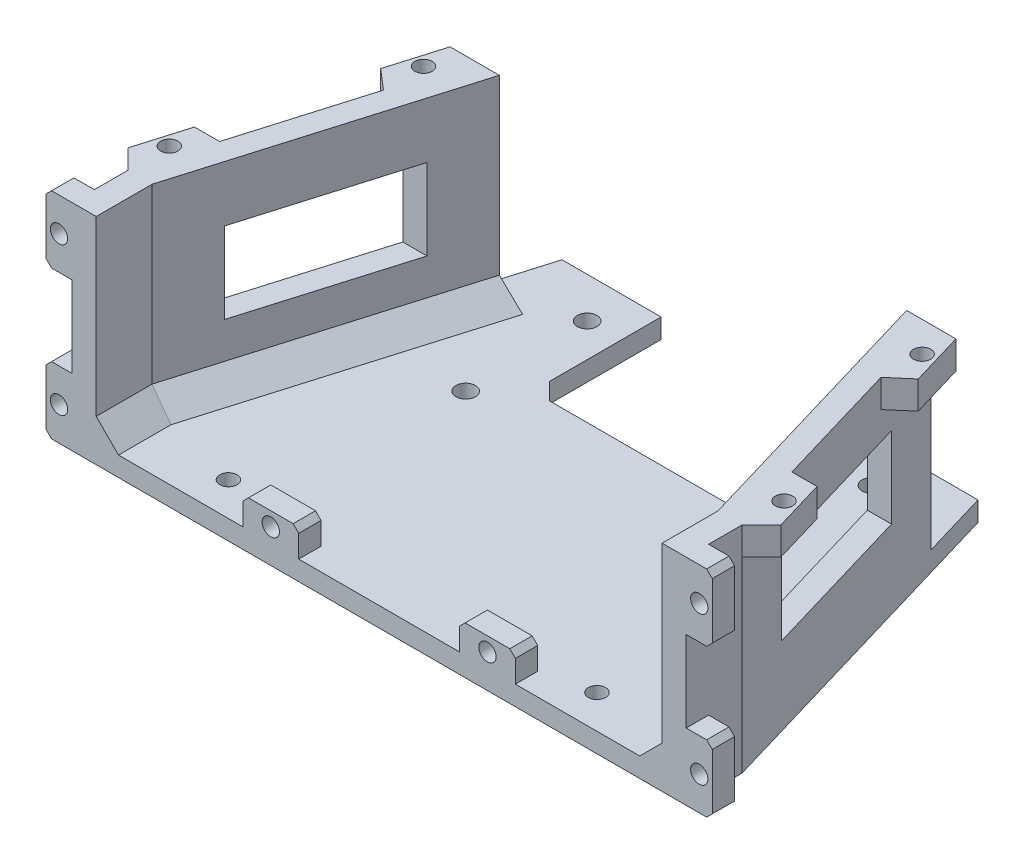
SolidWorks part; units mm, degrees
ref_plane "Front Plane" through (0, 0, 0) normal (0, 0, 1) x (1, 0, 0)
ref_plane "Top Plane" through (0, 0, 0) normal (0, 1, 0) x (1, 0, 0)
ref_plane "Right Plane" through (0, 0, 0) normal (1, 0, 0) x (0, 0, -1)
sketch "Sketch1" plane through (0, 0, 0) normal (0, 1, 0) x (1, 0, 0)
  line L0 (35.5, 70) -> (35.5, 46.9995)
  line L1 (0, 0) -> (110, 0)
  line L2 (0, 0) -> (0, 70)
  line L3 (0, 70) -> (35.5, 70)
  line L4 (110, 0) -> (110, 70)
  line L5 (35.5, 46.9995) -> (74.5, 46.9995)
  line L6 (74.5, 46.9995) -> (74.5, 70)
  line L7 (74.5, 70) -> (110, 70)
  dimension "D1" = 110
  dimension "D2" = 23.0005
  dimension "30" = 35.5
  dimension "D3" = 35.5
  dimension "D4" = 39
  dimension "60" = 70
extrude "Boss-Extrude1" add sketch "Sketch1" along normal blind 3.5
fillet "Fillet1" radius 3 2 edges at (35.5, 1.75, -46.9995) (74.5, 1.75, -46.9995) profile chamfer
sketch "Sketch3" plane through (0, 0, 0) normal (0, 0, 1) x (1, 0, 0)
  line L0 (55, 0) -> (55, 31.9215) construction
  line L1 (0, 0) -> (110, 0) construction
sketch "Sketch4" plane through (0, 3.5, 0) normal (0, 1, 0) x (1, 0, 0)
  line L0 (55, 46.9995) -> (55, 0) construction
  line L1 (71.5, 46.9995) -> (38.5, 46.9995) construction
  line L2 (0, 0) -> (110, 0) construction
  line L3 (110, 10) -> (105.67, 10)
  line L4 (0, 0) -> (4.33, 0)
  line L5 (0, 0) -> (0, 10)
  line L6 (0, 10) -> (4.33, 10)
  line L7 (4.33, 0) -> (4.33, 10)
  line L8 (105.67, 0) -> (105.67, 10)
  line L9 (110, 0) -> (105.67, 0)
  line L10 (110, 0) -> (110, 10)
  dimension "D1" = 4.33
  dimension "10" = 10
extrude "Boss-Extrude2" add sketch "Sketch4" along normal blind 35
sketch "Sketch5" plane through (0, 0, 0) normal (0, 0, 1) x (1, 0, 0)
  line L0 (4.33, 3.5) -> (105.67, 3.5) construction
  line L1 (40.6, 3.5) -> (30.6, 3.5)
  line L2 (40.6, 3.5) -> (40.6, 8.5)
  line L3 (40.6, 8.5) -> (30.6, 8.5)
  line L4 (30.6, 3.5) -> (30.6, 8.5)
  line L5 (55, 0) -> (55, 31.9215) construction
  line L6 (-2.3294, 38.5) -> (-2.3294, 26.5) construction
  line L7 (0, 38.5) -> (-4.6587, 38.5)
  line L8 (0, 38.5) -> (0, 26.5)
  line L9 (0, 26.5) -> (-4.6587, 26.5)
  line L10 (-4.6587, 38.5) -> (-4.6587, 26.5)
  line L11 (0, 0) -> (-4.6587, 0)
  line L12 (0, 0) -> (0, 12)
  line L13 (0, 12) -> (-4.6587, 12)
  line L14 (-4.6587, 0) -> (-4.6587, 12)
  line L15 (-2.3294, 26.5) -> (-2.3294, 12) construction
  line L16 (-2.3294, 12) -> (-2.3294, 0) construction
  line L17 (-2.3294, 0) -> (30.6, 6) construction
  line L18 (30.6, 6) -> (40.6, 6) construction
  line L19 (55, 0) -> (55, 31.9215) construction
  line L20 (69.4, 8.5) -> (79.4, 8.5)
  line L21 (79.4, 3.5) -> (79.4, 8.5)
  line L22 (69.4, 3.5) -> (79.4, 3.5)
  line L23 (69.4, 3.5) -> (69.4, 8.5)
  line L24 (110, 12) -> (114.6587, 12)
  line L25 (114.6587, 0) -> (114.6587, 12)
  line L26 (110, 0) -> (114.6587, 0)
  line L27 (110, 0) -> (110, 12)
  line L28 (110, 26.5) -> (114.6587, 26.5)
  line L29 (114.6587, 38.5) -> (114.6587, 26.5)
  line L30 (110, 38.5) -> (114.6587, 38.5)
  line L31 (110, 38.5) -> (110, 26.5)
  circle A0 centre (-2.3294, 32.5) radius 1.55
  circle A1 centre (-2.3294, 6) radius 1.55
  circle A2 centre (35.6, 6) radius 1.55
  circle A3 centre (74.4, 6) radius 1.55
  circle A4 centre (112.3294, 6) radius 1.55
  circle A5 centre (112.3294, 32.5) radius 1.55
  dimension "D5" = 3.1
  dimension "D6" = 3.1
  dimension "D7" = 3.1
  dimension "D1" = 14.4
  dimension "D2" = 10
  dimension "D3" = 12
  dimension "3.5" = 5
  dimension "D4" = 12
extrude "Boss-Extrude3" add sketch "Sketch5" against normal blind 4
fillet "Fillet2" radius 1 12 edges at (114.6587, 0, -2) (114.6587, 26.5, -2) (114.6587, 38.5, -2) (114.6587, 12, -2) (79.4, 8.5, -2) (69.4, 8.5, -2) (40.6, 8.5, -2) (30.6, 8.5, -2) (-4.6587, 0, -2) (-4.6587, 12, -2) (-4.6587, 26.5, -2) (-4.6587, 38.5, -2) profile chamfer
sketch "Sketch6" plane through (0, 3.5, 0) normal (0, 1, 0) x (1, 0, 0)
  line L0 (55, 46.9995) -> (55, 73.7007) construction
  line L1 (71.5, 46.9995) -> (38.5, 46.9995) construction
  line L2 (17.75, 70) -> (92.25, 70)
  line L3 (35.5, 70) -> (74.5, 70) construction
  line L4 (110, 70) -> (74.5, 70) construction
  line L5 (92.25, 70) -> (110, 10)
  line L6 (110, 10) -> (110, 70)
  line L7 (110, 70) -> (92.25, 70)
  line L8 (17.75, 70) -> (0, 10)
  line L9 (0, 10) -> (0, 70)
  line L10 (0, 70) -> (17.75, 70)
  point P4 (55, 70)
  point P14 (55, 70)
  line M8 (110, 10) -> (110, 70)
  line M9 (110, 70) -> (74.5, 70)
  line M15 (35.5, 70) -> (0, 70)
  line M16 (0, 70) -> (0, 10)
extrude "Cut-Extrude1" cut sketch "Sketch6" against normal blind 14 contours L8 M15 M16 | L5 M9 M8
sketch "Sketch8" plane through (0, 3.5, 0) normal (0, 1, 0) x (1, 0, 0)
  line L0 (14.2, 58) -> (95.8, 58) construction
  line L1 (17.75, 70) -> (0, 10) construction
  line L2 (92.25, 70) -> (110, 10) construction
  line L3 (35.5, 70) -> (17.75, 70) construction
  line L4 (0, 10) -> (14.2, 58)
  line L5 (14.2, 58) -> (18.53, 58)
  line L6 (18.53, 58) -> (4.33, 10)
  line L7 (4.33, 10) -> (0, 10)
  line L8 (55, 58) -> (55, 0) construction
  line L9 (40.6, 0) -> (69.4, 0) construction
  line L10 (91.47, 58) -> (105.67, 10)
  line L11 (95.8, 58) -> (91.47, 58)
  line L12 (110, 10) -> (95.8, 58)
  line L13 (105.67, 10) -> (110, 10)
  dimension "D1" = 12
  dimension "D2" = 4.33
extrude "Boss-Extrude4" add sketch "Sketch8" along normal blind 35
sketch "Sketch9" plane through (0, 0, 0) normal (-1, 0, 0) x (0, 0, 1)
  line L0 (-58, 38.5) -> (-10, 38.5) construction
  line L1 (-20, 28.5) -> (-48, 28.5)
  line L2 (-20, 28.5) -> (-20, 14)
  line L3 (-20, 14) -> (-48, 14)
  line L4 (-48, 28.5) -> (-48, 14)
  line L5 (-58, 38.5) -> (-58, 3.5) construction
  line L6 (-10, 0) -> (-70, 0) construction
  line L7 (-10, 38.5) -> (-10, 0) construction
  dimension "D1" = 10
  dimension "D2" = 14
  dimension "10" = 10
  dimension "D3" = 10
extrude "Cut-Extrude2" cut sketch "Sketch9" against normal blind 117
sketch "Sketch10" plane through (0, 3.5, 0) normal (0, 1, 0) x (1, 0, 0)
  line L0 (55, 46.9995) -> (55, 72.6447) construction
  line L1 (71.5, 46.9995) -> (38.5, 46.9995) construction
  line L2 (74.5, 70) -> (74.5, 49.9995) construction
  line L3 (92.25, 70) -> (74.5, 70) construction
  circle A0 centre (80.5, 62.75) radius 1.75
  circle A1 centre (80.5, 41) radius 1.75
  circle A2 centre (29.5, 41) radius 1.75
  circle A3 centre (29.5, 62.75) radius 1.75
  dimension "D1" = 6
  dimension "D2" = 6
  dimension "D3" = 21.75
  dimension "D4" = 7.25
  dimension "D5" = 3.5
  dimension "D6" = 3.5
extrude "Cut-Extrude3" cut sketch "Sketch10" against normal blind 117
fillet "Fillet3" radius 4 4 edges at (98.57, 3.5, -34) (11.43, 3.5, -34) (4.33, 3.5, -5) (105.67, 3.5, -5) profile chamfer
sketch "Sketch11" plane through (0, 38.5, 0) normal (0, 1, 0) x (1, 0, 0)
  line L0 (55, 46.9995) -> (55, 0) construction
  line L1 (71.5, 46.9995) -> (38.5, 46.9995) construction
  line L2 (40.6, 0) -> (69.4, 0) construction
  line L3 (110, 6.01) -> (55, 6.01) construction
  line L4 (110, 4) -> (110, 10) construction
  line L5 (79.4, 0) -> (101.67, 0) construction
  circle A0 centre (88, 6.01) radius 1.55
  circle A1 centre (22, 6.01) radius 1.55
  dimension "D1" = 22
  dimension "D3" = 3.1
  dimension "D2" = 6.01
extrude "Cut-Extrude4" cut sketch "Sketch11" against normal blind 95
sketch "Sketch12" plane through (0, 38.5, 0) normal (0, 1, 0) x (1, 0, 0)
  line L0 (14.2, 58) -> (9.7, 58)
  line L1 (14.2, 58) -> (11.3632, 48.4108)
  line L4 (6.8632, 48.4108) -> (9.7, 58)
  line L5 (55, 0) -> (55, 70.416) construction
  line L7 (14.2, 58) -> (0, 10) construction
  line L8 (40.6, 0) -> (69.4, 0) construction
  line L9 (3.7502, 22.6767) -> (0.9134, 13.0875)
  line L11 (-3.4724, 13.4734) -> (-0.7498, 22.6767)
  line L12 (-0.7498, 22.6767) -> (3.7502, 22.6767)
  line L13 (6.8632, 48.4108) -> (10.45, 45.324)
  line L14 (10.45, 45.324) -> (11.3632, 48.4108)
  line L15 (-3.4724, 13.4734) -> (0, 10)
  line L16 (0, 10) -> (0.9134, 13.0875)
  line L17 (110.7498, 22.6767) -> (106.2498, 22.6767)
  line L18 (113.4724, 13.4734) -> (110.7498, 22.6767)
  line L19 (113.4724, 13.4734) -> (110, 10)
  line L20 (110, 10) -> (109.0866, 13.0875)
  line L21 (106.2498, 22.6767) -> (109.0866, 13.0875)
  line L22 (103.1368, 48.4108) -> (99.55, 45.324)
  line L23 (99.55, 45.324) -> (98.6368, 48.4108)
  line L24 (95.8, 58) -> (98.6368, 48.4108)
  line L25 (95.8, 58) -> (100.3, 58)
  line L26 (103.1368, 48.4108) -> (100.3, 58)
  line L27 (12.4195, 51.9813) -> (8.2816, 53.2054) construction
  line L28 (-2.1111, 18.0751) -> (2.0267, 16.8509) construction
  circle A0 centre (-0.0422, 17.463) radius 1.55
  circle A1 centre (10.3505, 52.5933) radius 1.55
  circle A2 centre (110.0422, 17.463) radius 1.55
  circle A3 centre (99.6495, 52.5933) radius 1.55
  dimension "D5" = 3.1
  dimension "D6" = 3.1
  dimension "D1" = 4.5
  dimension "D2" = 10
  dimension "40" = 4.5
  dimension "D3" = 10
  dimension "D4" = 4.5
extrude "Boss-Extrude5" add sketch "Sketch12" against normal blind 5
